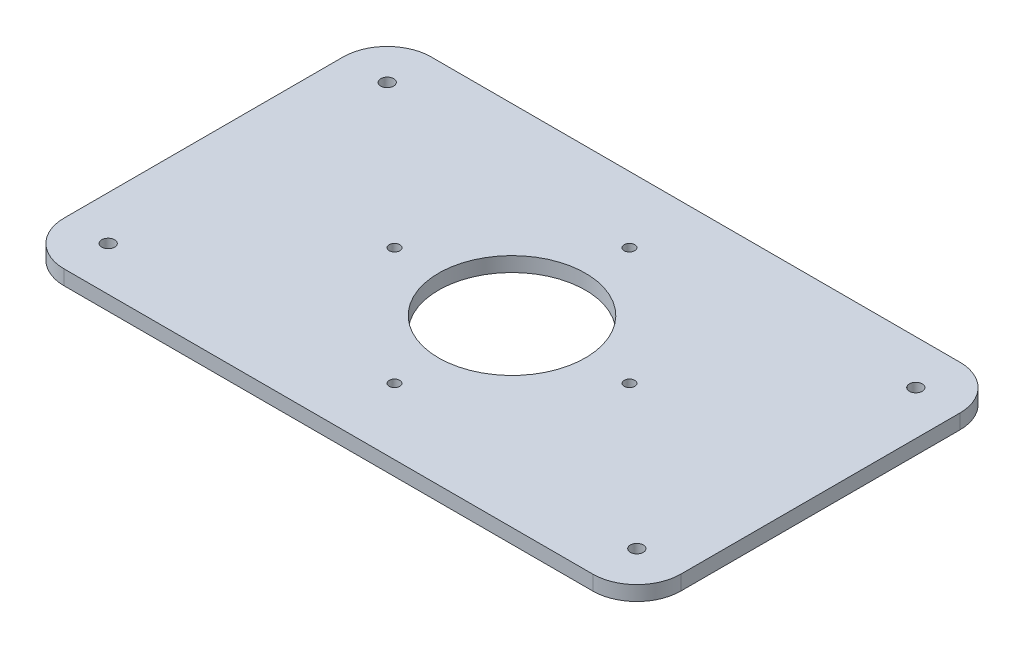
SolidWorks part; units mm, degrees
ref_plane "前视基准面" through (0, 0, 0) normal (0, 0, 1) x (1, 0, 0)
ref_plane "上视基准面" through (0, 0, 0) normal (0, 1, 0) x (1, 0, 0)
ref_plane "右视基准面" through (0, 0, 0) normal (1, 0, 0) x (0, 0, -1)
sketch "草图1" plane through (0, 0, 0) normal (0, 1, 0) x (1, 0, 0)
  circle A0 centre (0, 0) radius 25
  circle A1 centre (0, 0) radius 60
extrude "凸台-拉伸1" add sketch "草图1" along normal blind 5
sketch "草图2" plane through (0, 5, 0) normal (0, 1, 0) x (1, 0, 0)
  line L0 (-106.8682, 0) -> (92.1796, 0) construction
  line L2 (0, 64.4794) -> (0, -68.2962) construction
  circle A0 centre (0, 40) radius 1.8
  circle A1 centre (40, 0) radius 1.8
  circle A2 centre (0, -40) radius 1.8
  circle A3 centre (-40, 0) radius 1.8
  point P16 (0, 0)
  dimension "D1" = 4
  dimension "D2" = 40
extrude "切除-拉伸1" cut sketch "草图2" against normal blind 5
sketch "草图4" plane through (0, 0, 0) normal (0, 1, 0) x (1, 0, 0)
  line L0 (-140.1, 0) -> (119.115, 0) construction
  line L1 (-105, 62.5) -> (105, 62.5)
  line L2 (-105, 62.5) -> (-105, -62.5)
  line L3 (-105, -62.5) -> (105, -62.5)
  line L4 (105, 62.5) -> (105, -62.5)
  line L5 (0, 91.2349) -> (0, -96.2313) construction
  circle A0 centre (0, 0) radius 60
  dimension "D1" = 210
  dimension "D2" = 125
extrude "凸台-拉伸2" add sketch "草图4" along normal blind 5
sketch "草图5" plane through (0, 5, 0) normal (0, 1, 0) x (1, 0, 0)
  line L0 (105, 62.5) -> (-105, 62.5) construction
  line L1 (-105, 62.5) -> (-105, -62.5) construction
  line L2 (-199.7774, 0) -> (140.1036, 0) construction
  line L4 (0, 109.7803) -> (0, -113.9964) construction
  circle A0 centre (-90, 47.5) radius 2.2
  circle A4 centre (90, 47.5) radius 2.2
  circle A5 centre (90, -47.5) radius 2.2
  circle A6 centre (-90, -47.5) radius 2.2
  point P15 (-15, 15)
  dimension "D1" = 15
  dimension "D2" = 15
extrude "切除-拉伸2" cut sketch "草图5" against normal blind 5
fillet "圆角1" radius 15 4 edges at (-105, 2.5, 62.5) (105, 2.5, 62.5) (105, 2.5, -62.5) (-105, 2.5, -62.5)
